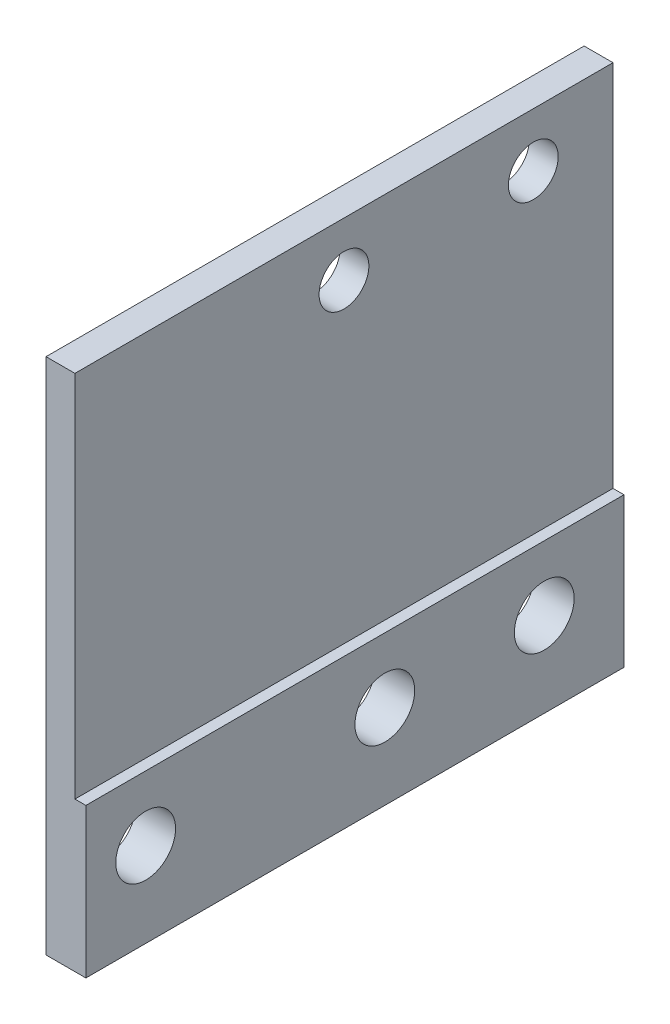
SolidWorks part; units mm, degrees
material "Aluminum"
ref_plane "Front Plane" through (0, 0, 0) normal (0, 0, 1) x (1, 0, 0)
ref_plane "Top Plane" through (0, 0, 0) normal (0, 1, 0) x (1, 0, 0)
ref_plane "Right Plane" through (0, 0, 0) normal (1, 0, 0) x (0, 0, -1)
sketch "Sketch1" plane through (0, 0, 0) normal (0, 0, 1) x (1, 0, 0)
  line L1 (0, 0) -> (2, 0)
  line L2 (0, 0) -> (0, 7.5)
  line L3 (1.45, 7.5) -> (2, 7.5)
  line L4 (2, 0) -> (2, 7.5)
  line L6 (0, 7.5) -> (0, 26)
  line L7 (0, 26) -> (1.45, 26)
  line L8 (1.45, 7.5) -> (1.45, 26)
  dimension "D1" = 2
  dimension "D2" = 1.45
  dimension "D3" = 7.5
  dimension "D4" = 18.5
extrude "Boss-Extrude1" add sketch "Sketch1" along normal blind 22 and the other way blind 5
hole_wizard "Tap Drill for M3x0.5 Tap1" positions "Sketch6" profile "Sketch4" hole size "M3x0.5" standard "ANSI Metric" end condition through all
sketch "Sketch6" plane through (2, 0, 0) normal (1, 0, 0) x (0, 0, -1)
  line L4 (5, 7.5) -> (5, 26) construction
  point P0 (-7, 4.25)
  point P3 (-19, 4.25)
  point P21 (1, 4.25)
  dimension "D1" = 12
  dimension "D2" = 12
  dimension "D3" = 8
sketch "Sketch4" plane through (2, 4.25, 7) normal (0, 1, 0) x (0, 0, -1)
  line L0 (0, 0) -> (0, 2)
  line L1 (0, 2) -> (1.5, 2)
  line L2 (1.5, 2) -> (1.5, 0)
  line L5 (1.5, 0) -> (0, 0)
  line L11 (0, -6.35) -> (0, 107.95) construction
  dimension "Thru Hole Dia." = 3
  dimension "Thru Hole Depth" = 2
hole_wizard "Tap Drill for M2.5x0.45 Tap1" positions "Sketch8" profile "Sketch7" hole size "M2.5x0.45" standard "ANSI Metric" end condition through all
sketch "Sketch8" plane through (1.45, 0, 0) normal (1, 0, 0) x (0, 0, -1)
  point P0 (1, 23.2972)
  point P2 (-8.5, 23.2972)
sketch "Sketch7" plane through (1.45, 23.2972, -1) normal (0, 1, 0) x (0, 0, -1)
  line L0 (0, 0) -> (0, 1.45)
  line L1 (0, 1.45) -> (1.25, 1.45)
  line L2 (1.25, 1.45) -> (1.25, 0)
  line L5 (1.25, 0) -> (0, 0)
  line L11 (0, -6.35) -> (0, 107.95) construction
  dimension "Thru Hole Dia." = 2.5
  dimension "Thru Hole Depth" = 1.45
